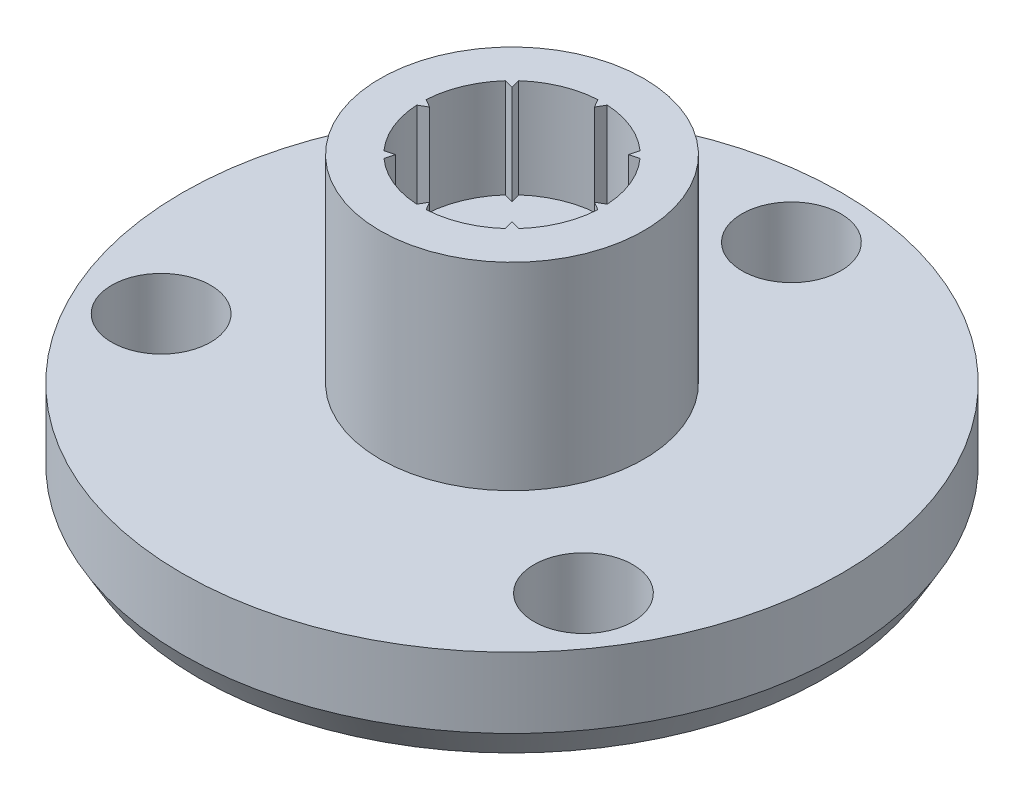
SolidWorks part; units mm, degrees
ref_plane "Front Plane" through (0, 0, 0) normal (0, 0, 1) x (1, 0, 0)
ref_plane "Top Plane" through (0, 0, 0) normal (0, 1, 0) x (1, 0, 0)
ref_plane "Right Plane" through (0, 0, 0) normal (1, 0, 0) x (0, 0, -1)
sketch "Sketch1" plane through (0, 0, 0) normal (0, 1, 0) x (1, 0, 0)
  circle A0 centre (0, 0) radius 10
  dimension "D1" = 20
extrude "Boss-Extrude1" add sketch "Sketch1" along normal blind 3 contours A0
sketch "Sketch2" plane through (0, 3, 0) normal (0, 1, 0) x (1, 0, 0)
  circle A0 centre (0, 0) radius 4
  dimension "D1" = 8
extrude "Boss-Extrude2" add sketch "Sketch2" along normal blind 3
sketch "Sketch3" plane through (0, 0, 0) normal (0, -1, 0) x (1, 0, 0)
  circle A0 centre (0, 0) radius 2.5
  dimension "D1" = 5
extrude "Cut-Extrude1" cut sketch "Sketch3" against normal blind 5
sketch "Sketch4" plane through (0, 0, 0) normal (0, -1, 0) x (1, 0, 0)
  circle A0 centre (-7.1417, 3.5) radius 1.5
  circle A1 centre (0, 0) radius 10 construction
  circle A2 centre (6.602, 4.4349) radius 1.5
  circle A3 centre (0.5398, -7.9349) radius 1.5
  point P11 (0, 0)
  dimension "D1" = 3
  dimension "D3" = 3
  dimension "D2" = 3.5
extrude "Cut-Extrude2" cut sketch "Sketch4" against normal blind 3
sketch "Sketch5" plane through (0, 6, 0) normal (0, 1, 0) x (1, 0, 0)
  circle A0 centre (0, 0) radius 0.925
  dimension "D1" = 1.85
extrude "Cut-Extrude3" cut sketch "Sketch5" against normal blind 1
chamfer "Chamfer1" distance 0.5 angle 60 1 edges at (0, 0, 10)
sketch "Sketch6" plane through (0, 6, 0) normal (0, 1, 0) x (1, 0, 0)
  circle A0 centre (0, 0) radius 4
  dimension "D1" = 8
extrude "Boss-Extrude3" add sketch "Sketch6" along normal blind 3
sketch "Sketch7" plane through (0, 9, 0) normal (0, 1, 0) x (1, 0, 0)
  circle A0 centre (0, 0) radius 2.75
  dimension "D1" = 5.5
extrude "Cut-Extrude4" cut sketch "Sketch7" against normal blind 3
sketch "Sketch8" plane through (0, 6, 0) normal (0, 1, 0) x (1, 0, 0)
  line L0 (0, 0) -> (0, 2.9843) construction
  line L1 (0, 2.5) -> (0.2165, 2.875)
  line L2 (0.2165, 2.875) -> (-0.2165, 2.875)
  line L3 (-0.2165, 2.875) -> (0, 2.5)
  line L4 (0, 2.9843) -> (1.4248, 2.9843) construction
  line L5 (1.4248, 2.9843) -> (-1.3048, 2.9843) construction
  line L6 (1.7678, 1.7678) -> (2.186, 1.8798)
  line L7 (2.186, 1.8798) -> (1.8798, 2.186)
  line L8 (1.8798, 2.186) -> (1.7678, 1.7678)
  line L9 (2.5, 0) -> (2.875, -0.2165)
  line L10 (2.875, -0.2165) -> (2.875, 0.2165)
  line L11 (2.875, 0.2165) -> (2.5, 0)
  line L12 (1.7678, -1.7678) -> (1.8798, -2.186)
  line L13 (1.8798, -2.186) -> (2.186, -1.8798)
  line L14 (2.186, -1.8798) -> (1.7678, -1.7678)
  line L15 (0, -2.5) -> (-0.2165, -2.875)
  line L16 (-0.2165, -2.875) -> (0.2165, -2.875)
  line L17 (0.2165, -2.875) -> (0, -2.5)
  line L18 (-1.7678, -1.7678) -> (-2.186, -1.8798)
  line L19 (-2.186, -1.8798) -> (-1.8798, -2.186)
  line L20 (-1.8798, -2.186) -> (-1.7678, -1.7678)
  line L21 (-2.5, 0) -> (-2.875, 0.2165)
  line L22 (-2.875, 0.2165) -> (-2.875, -0.2165)
  line L23 (-2.875, -0.2165) -> (-2.5, 0)
  line L24 (-1.7678, 1.7678) -> (-1.8798, 2.186)
  line L25 (-1.8798, 2.186) -> (-2.186, 1.8798)
  line L26 (-2.186, 1.8798) -> (-1.7678, 1.7678)
  circle A0 centre (0, 2.75) radius 0.125 construction
  circle A1 centre (0, 0) radius 2.75 construction
  circle A2 centre (0, 0) radius 2.75 construction
  point P37 (0, 0)
  dimension "D1" = 2.5
  dimension "D2" = 0
  dimension "D3" = 0.1093
  dimension "D4" = 0
  dimension "D5" = 8
extrude "Boss-Extrude6" add sketch "Sketch8" along normal blind 3
